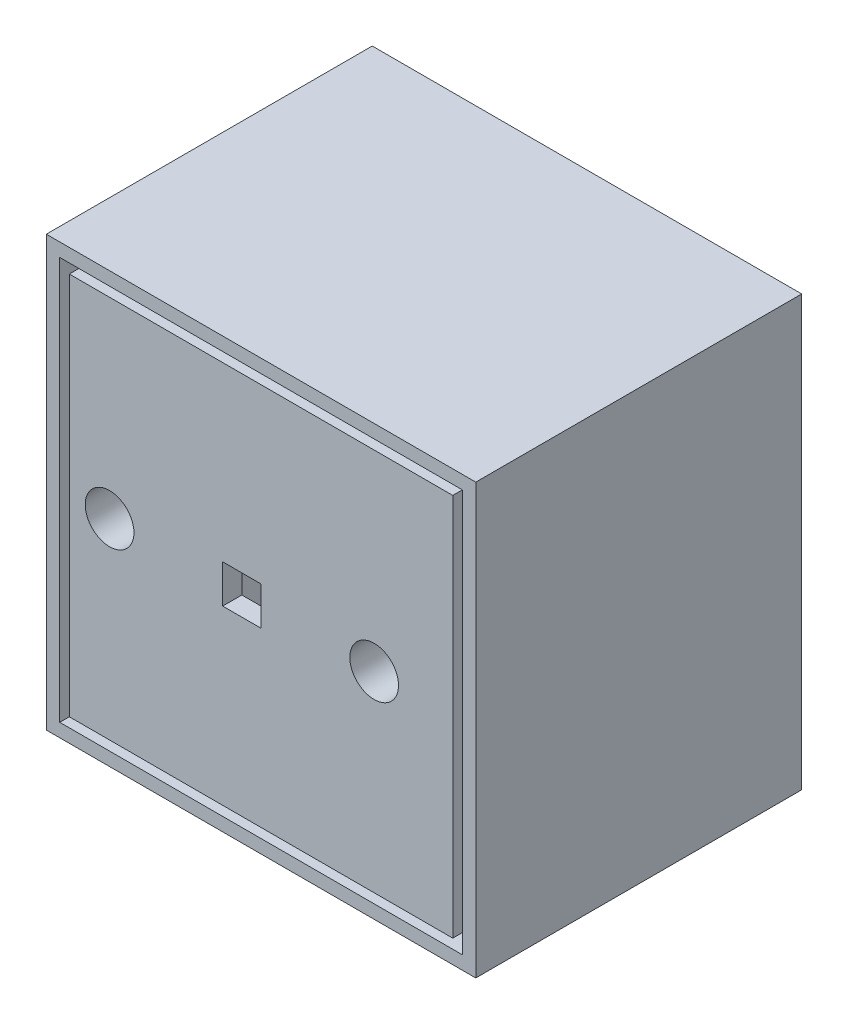
SolidWorks part; units mm, degrees
ref_plane "Front Plane" through (0, 0, 0) normal (0, 0, 1) x (1, 0, 0)
ref_plane "Top Plane" through (0, 0, 0) normal (0, 1, 0) x (1, 0, 0)
ref_plane "Right Plane" through (0, 0, 0) normal (1, 0, 0) x (0, 0, -1)
sketch "Sketch2" plane through (0, 0, 0) normal (0, 0, 1) x (1, 0, 0)
  line L1 (-56, -56) -> (56, -56)
  line L2 (-56, -56) -> (-56, 56)
  line L3 (-56, 56) -> (56, 56)
  line L4 (56, -56) -> (56, 56)
  line L5 (-56, -56) -> (56, 56) construction
  line L6 (-56, 56) -> (56, -56) construction
  line L11 (-5, -5) -> (5, 5) construction
  line L12 (-5, 5) -> (5, -5) construction
  line L13 (-10, 5) -> (0, 5)
  line L14 (-10, 5) -> (-10, -5)
  line L15 (-10, -5) -> (0, -5)
  line L16 (0, 5) -> (0, -5)
  line L17 (-10, 5) -> (0, -5) construction
  line L18 (-10, -5) -> (0, 5) construction
  point P0 (0, 0)
  point P6 (0, 0)
  point P11 (-5, 0)
  dimension "D2" = 112
  dimension "D3" = 112
  dimension "D5" = 10
  dimension "D6" = 10
  dimension "D7" = 5
extrude "Boss-Extrude1" add sketch "Sketch2" along normal blind 5
sketch "Sketch3" plane through (0, 0, 5) normal (0, 0, 1) x (1, 0, 0)
  line L1 (-50, 50) -> (50, 50)
  line L2 (-50, 50) -> (-50, -50)
  line L3 (-50, -50) -> (50, -50)
  line L4 (50, 50) -> (50, -50)
  line L5 (-50, 50) -> (50, -50) construction
  line L6 (-50, -50) -> (50, 50) construction
  line L8 (-52.5, -52.5) -> (52.5, -52.5)
  line L9 (-52.5, -52.5) -> (-52.5, 52.5)
  line L10 (-52.5, 52.5) -> (52.5, 52.5)
  line L11 (52.5, -52.5) -> (52.5, 52.5)
  line L12 (-52.5, -52.5) -> (52.5, 52.5) construction
  line L13 (-52.5, 52.5) -> (52.5, -52.5) construction
  circle A0 centre (-39.5, 0) radius 6.35
  circle A3 centre (29.5, 0) radius 6.35
  point P4 (0, 0)
  point P12 (0, 0)
  dimension "D3" = 12.7
  dimension "D4" = 105
  dimension "D7" = 12.7
  dimension "D1" = 100
  dimension "D2" = 100
  dimension "D5" = 39.5
  dimension "D6" = 105
  dimension "D8" = 29.5
extrude "Boss-Extrude2" add sketch "Sketch3" along normal blind 20
sketch "Sketch4" plane through (0, 0, 0) normal (0, 0, -1) x (-1, 0, 0)
  line L5 (-26.7354, -24.6573) -> (26.7354, 24.6573) construction
  line L6 (-26.7354, 24.6573) -> (26.7354, -24.6573) construction
  line L7 (-20, 25) -> (30, 25)
  line L8 (-20, 25) -> (-20, -25)
  line L9 (-20, -25) -> (30, -25)
  line L10 (30, 25) -> (30, -25)
  line L11 (-20, 25) -> (30, -25) construction
  line L12 (-20, -25) -> (30, 25) construction
  point P0 (0, 0)
  point P6 (5, 0)
  dimension "D1" = 50
  dimension "D2" = 50
  dimension "D3" = 25
  dimension "D4" = 5
extrude "Cut-Extrude1" cut sketch "Sketch4" against normal blind 20
sketch "Sketch8" plane through (0, 0, 0) normal (0, 0, -1) x (-1, 0, 0)
  line L1 (-50, -50) -> (50, -50)
  line L2 (-50, -50) -> (-50, 50)
  line L3 (-50, 50) -> (50, 50)
  line L4 (50, -50) -> (50, 50)
  line L5 (-50, -50) -> (50, 50) construction
  line L6 (-50, 50) -> (50, -50) construction
  point P0 (0, 0)
  line M7 (-56, 56) -> (-56, -56)
  line M8 (-56, -56) -> (56, -56)
  line M9 (56, -56) -> (56, 56)
  line M10 (56, 56) -> (-56, 56)
  dimension "D1" = 100
  dimension "D2" = 100
extrude "Boss-Extrude3" add sketch "Sketch8" along normal blind 60 contours L4 L1 L2 L3 M10 M7 M8 M9
